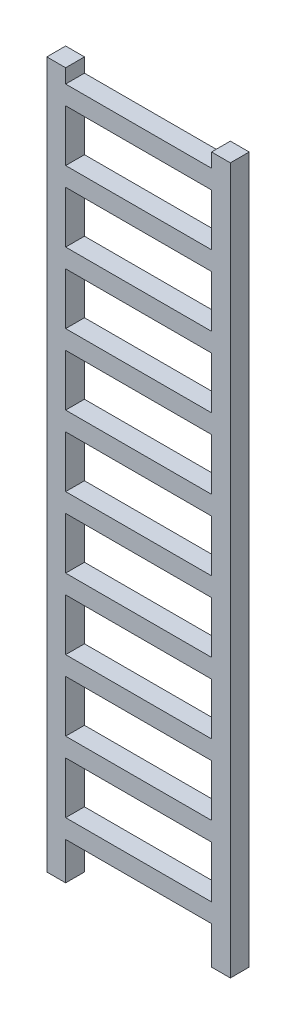
SolidWorks part; units mm, degrees
ref_plane "前视基准面" through (0, 0, 0) normal (0, 0, 1) x (1, 0, 0)
ref_plane "上视基准面" through (0, 0, 0) normal (0, 1, 0) x (1, 0, 0)
ref_plane "右视基准面" through (0, 0, 0) normal (1, 0, 0) x (0, 0, -1)
other "Configuration Table"
sketch "草图1" plane through (0, 0, 0) normal (0, 0, 1) x (1, 0, 0)
  line L1 (-390, -1500) -> (-310, -1500)
  line L2 (-390, -1500) -> (-390, 1500)
  line L3 (-390, 1500) -> (-310, 1500)
  line L4 (-310, -1500) -> (-310, 1500)
  line L5 (-390, -1500) -> (-310, 1500) construction
  line L6 (-390, 1500) -> (-310, -1500) construction
  point P0 (-350, 0)
extrude "凸台-拉伸1" add sketch "草图1" along normal blind 80
sketch "草图2" plane through (0, 0, 0) normal (0, 0, 1) x (1, 0, 0)
  line L1 (310, -1500) -> (390, -1500)
  line L2 (310, -1500) -> (310, 1500)
  line L3 (310, 1500) -> (390, 1500)
  line L4 (390, -1500) -> (390, 1500)
  line L5 (310, -1500) -> (390, 1500) construction
  line L6 (310, 1500) -> (390, -1500) construction
  point P0 (350, 0)
extrude "凸台-拉伸2" add sketch "草图2" along normal blind 80
sketch "草图3" plane through (0, 0, 0) normal (0, 0, 1) x (1, 0, 0)
  line L1 (-360, 1360) -> (360, 1360)
  line L2 (-360, 1360) -> (-360, 1440)
  line L3 (-360, 1440) -> (360, 1440)
  line L4 (360, 1360) -> (360, 1440)
  line L5 (-360, 1360) -> (360, 1440) construction
  line L6 (-360, 1440) -> (360, 1360) construction
  point P0 (0, 1400)
extrude "凸台-拉伸3" add sketch "草图3" along normal blind 80
sketch "草图4" plane through (0, 0, 0) normal (0, 0, 1) x (1, 0, 0)
  line L1 (-360, 1060) -> (360, 1060)
  line L2 (-360, 1060) -> (-360, 1140)
  line L3 (-360, 1140) -> (360, 1140)
  line L4 (360, 1060) -> (360, 1140)
  line L5 (-360, 1060) -> (360, 1140) construction
  line L6 (-360, 1140) -> (360, 1060) construction
  point P0 (0, 1100)
extrude "凸台-拉伸4" add sketch "草图4" along normal blind 80
sketch "草图5" plane through (0, 0, 0) normal (0, 0, 1) x (1, 0, 0)
  line L1 (-360, 760) -> (360, 760)
  line L2 (-360, 760) -> (-360, 840)
  line L3 (-360, 840) -> (360, 840)
  line L4 (360, 760) -> (360, 840)
  line L5 (-360, 760) -> (360, 840) construction
  line L6 (-360, 840) -> (360, 760) construction
  point P0 (0, 800)
extrude "凸台-拉伸5" add sketch "草图5" along normal blind 80
sketch "草图6" plane through (0, 0, 0) normal (0, 0, 1) x (1, 0, 0)
  line L1 (-360, 460) -> (360, 460)
  line L2 (-360, 460) -> (-360, 540)
  line L3 (-360, 540) -> (360, 540)
  line L4 (360, 460) -> (360, 540)
  line L5 (-360, 460) -> (360, 540) construction
  line L6 (-360, 540) -> (360, 460) construction
  point P0 (0, 500)
extrude "凸台-拉伸6" add sketch "草图6" along normal blind 80
sketch "草图7" plane through (0, 0, 0) normal (0, 0, 1) x (1, 0, 0)
  line L1 (-360, 160) -> (360, 160)
  line L2 (-360, 160) -> (-360, 240)
  line L3 (-360, 240) -> (360, 240)
  line L4 (360, 160) -> (360, 240)
  line L5 (-360, 160) -> (360, 240) construction
  line L6 (-360, 240) -> (360, 160) construction
  point P0 (0, 200)
extrude "凸台-拉伸7" add sketch "草图7" along normal blind 80
sketch "草图8" plane through (0, 0, 0) normal (0, 0, 1) x (1, 0, 0)
  line L1 (-360, -140) -> (360, -140)
  line L2 (-360, -140) -> (-360, -60)
  line L3 (-360, -60) -> (360, -60)
  line L4 (360, -140) -> (360, -60)
  line L5 (-360, -140) -> (360, -60) construction
  line L6 (-360, -60) -> (360, -140) construction
  point P0 (0, -100)
extrude "凸台-拉伸8" add sketch "草图8" along normal blind 80
sketch "草图9" plane through (0, 0, 0) normal (0, 0, 1) x (1, 0, 0)
  line L1 (-360, -440) -> (360, -440)
  line L2 (-360, -440) -> (-360, -360)
  line L3 (-360, -360) -> (360, -360)
  line L4 (360, -440) -> (360, -360)
  line L5 (-360, -440) -> (360, -360) construction
  line L6 (-360, -360) -> (360, -440) construction
  point P0 (0, -400)
extrude "凸台-拉伸9" add sketch "草图9" along normal blind 80
sketch "草图10" plane through (0, 0, 0) normal (0, 0, 1) x (1, 0, 0)
  line L1 (-360, -740) -> (360, -740)
  line L2 (-360, -740) -> (-360, -660)
  line L3 (-360, -660) -> (360, -660)
  line L4 (360, -740) -> (360, -660)
  line L5 (-360, -740) -> (360, -660) construction
  line L6 (-360, -660) -> (360, -740) construction
  point P0 (0, -700)
extrude "凸台-拉伸10" add sketch "草图10" along normal blind 80
sketch "草图11" plane through (0, 0, 0) normal (0, 0, 1) x (1, 0, 0)
  line L1 (-360, -1040) -> (360, -1040)
  line L2 (-360, -1040) -> (-360, -960)
  line L3 (-360, -960) -> (360, -960)
  line L4 (360, -1040) -> (360, -960)
  line L5 (-360, -1040) -> (360, -960) construction
  line L6 (-360, -960) -> (360, -1040) construction
  point P0 (0, -1000)
extrude "凸台-拉伸11" add sketch "草图11" along normal blind 80
sketch "草图12" plane through (0, 0, 0) normal (0, 0, 1) x (1, 0, 0)
  line L1 (-360, -1340) -> (360, -1340)
  line L2 (-360, -1340) -> (-360, -1260)
  line L3 (-360, -1260) -> (360, -1260)
  line L4 (360, -1340) -> (360, -1260)
  line L5 (-360, -1340) -> (360, -1260) construction
  line L6 (-360, -1260) -> (360, -1340) construction
  point P0 (0, -1300)
extrude "凸台-拉伸12" add sketch "草图12" along normal blind 80
